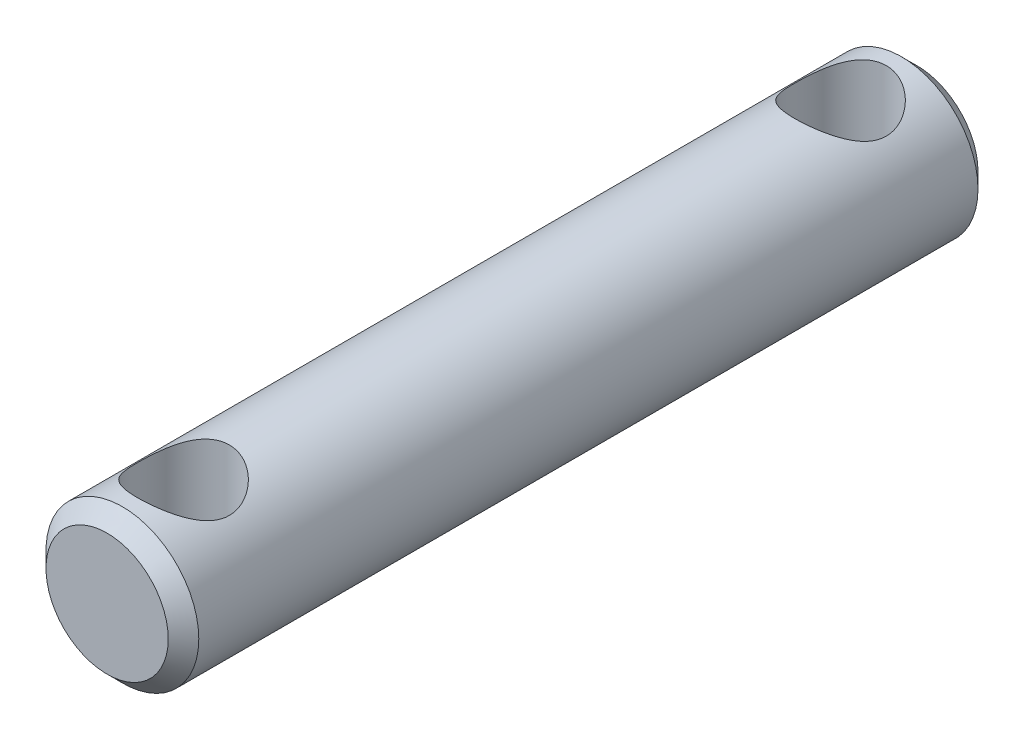
SolidWorks part; units mm, degrees
ref_plane "Vorne" through (0, 0, 0) normal (0, 0, 1) x (1, 0, 0)
ref_plane "Oben" through (0, 0, 0) normal (0, 1, 0) x (1, 0, 0)
ref_plane "Rechts" through (0, 0, 0) normal (1, 0, 0) x (0, 0, -1)
ref_plane "E_Boden" through (0, 1, 0) normal (0, 1, 0) x (1, 0, 0)
sketch "Skizze1" plane through (0, 0, 0) normal (0, 0, 1) x (1, 0, 0)
  circle A0 centre (0, 0) radius 5
  dimension "D1" = 10
extrude "Aufsatz-Linear austragen1" add sketch "Skizze1" along normal blind 53
ref_plane "Mantel" through (0, 5, 0) normal (0, 1, 0) x (1, 0, 0)
sketch "Skizze2" plane through (0, 5, 0) normal (0, 1, 0) x (1, 0, 0)
  line L0 (0, 8.7773) -> (0, -55.2536) construction
  line L1 (-5, -26.5) -> (5, -26.5) construction
  line L2 (-5, 0) -> (-5, -53) construction
  line L3 (5, -53) -> (5, 0) construction
  circle A0 centre (0, -5) radius 3
  circle A1 centre (0, -48) radius 3
  point P13 (0, 0)
  dimension "D1" = 6
  dimension "D2" = 6
  dimension "D3" = 43
extrude "Schnitt-Linear austragen1" cut sketch "Skizze2" against normal blind 47
chamfer "Fase1" distance 1 angle 45 2 edges at (5, 0, 53) (5, 0, 0)
